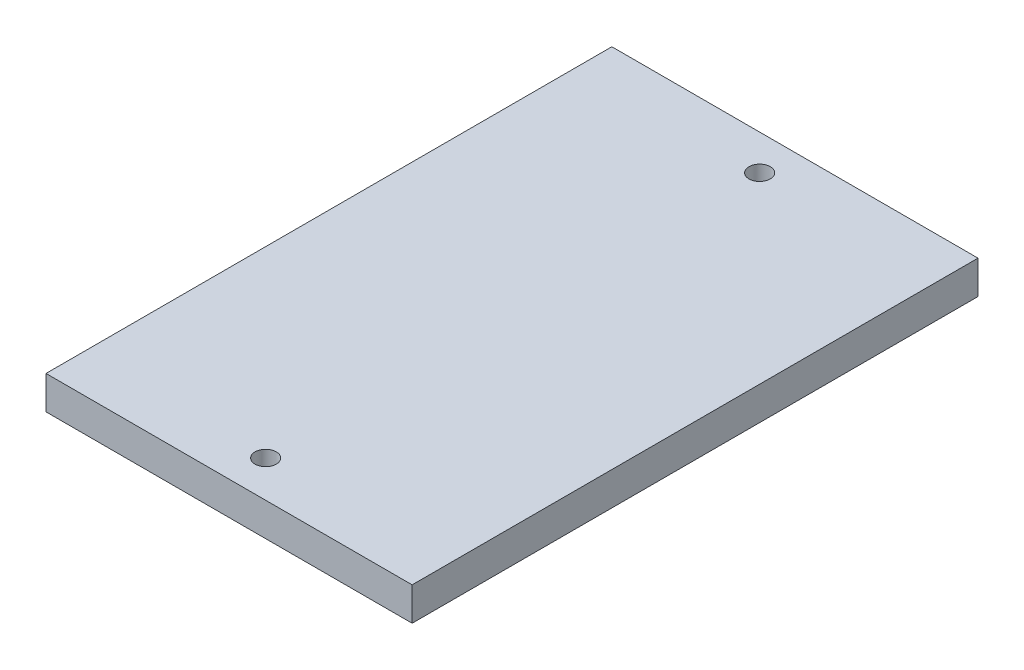
SolidWorks part; units mm, degrees
ref_plane "Front Plane" through (0, 0, 0) normal (0, 0, 1) x (1, 0, 0)
ref_plane "Top Plane" through (0, 0, 0) normal (0, 1, 0) x (1, 0, 0)
ref_plane "Right Plane" through (0, 0, 0) normal (1, 0, 0) x (0, 0, -1)
sketch "Sketch1" plane through (0, 0, 0) normal (0, 1, 0) x (1, 0, 0)
  line L1 (-27.5, -42.5) -> (27.5, -42.5)
  line L2 (-27.5, -42.5) -> (-27.5, 42.5)
  line L3 (-27.5, 42.5) -> (27.5, 42.5)
  line L4 (27.5, -42.5) -> (27.5, 42.5)
  line L5 (-27.5, -42.5) -> (27.5, 42.5) construction
  line L6 (-27.5, 42.5) -> (27.5, -42.5) construction
  circle A0 centre (0, -37) radius 1.6
  circle A1 centre (0, 37.2) radius 1.6
  point P0 (0, 0)
  point P9 (0, 0)
  dimension "D3" = 3.2
  dimension "D4" = 5.5
  dimension "D5" = 3.2
  dimension "D6" = 74.2
  dimension "D1" = 55
  dimension "D2" = 85
extrude "Boss-Extrude1" add sketch "Sketch1" along normal blind 5
